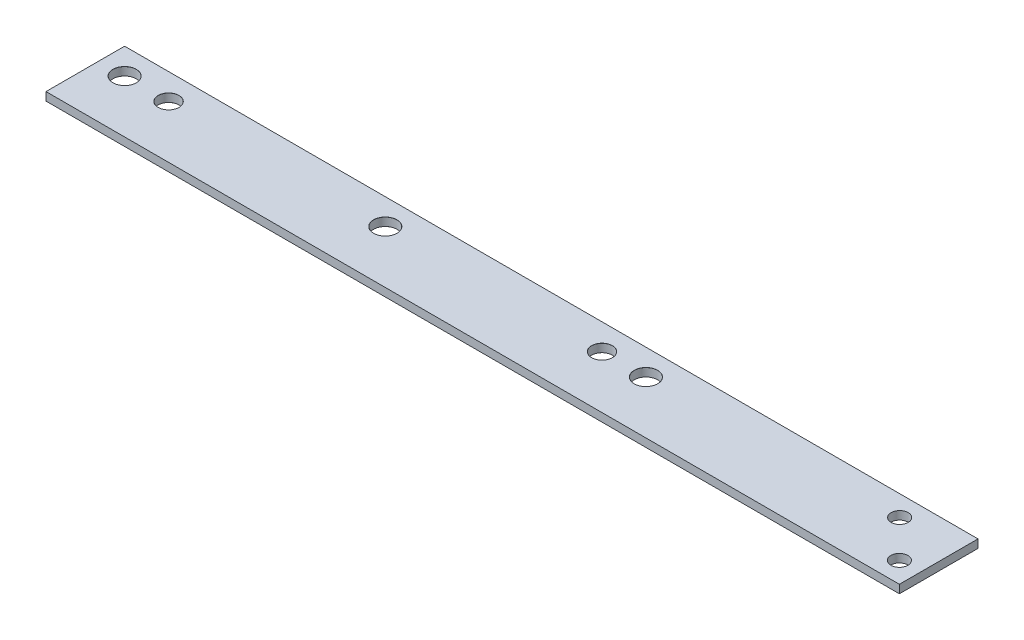
SolidWorks part; units mm, degrees
material "1.2316 (X36CrMo17)"
ref_plane "Front Plane" through (0, 0, 0) normal (0, 0, 1) x (1, 0, 0)
ref_plane "Top Plane" through (0, 0, 0) normal (0, 1, 0) x (1, 0, 0)
ref_plane "Right Plane" through (0, 0, 0) normal (1, 0, 0) x (0, 0, -1)
sketch "Sketch1" plane through (0, 0, 0) normal (0, 1, 0) x (1, 0, 0)
  line L1 (-165, 15.2) -> (165, 15.2)
  line L2 (-165, 15.2) -> (-165, -15.2)
  line L3 (-165, -15.2) -> (165, -15.2)
  line L4 (165, 15.2) -> (165, -15.2)
  line L5 (-165, 15.2) -> (165, -15.2) construction
  line L6 (-165, -15.2) -> (165, 15.2) construction
  point P0 (0, 0)
  dimension "D1" = 30.4
  dimension "D2" = 330
extrude "Boss-Extrude1" add sketch "Sketch1" against normal blind 3.2
sketch "Sketch2" plane through (0, 0, 0) normal (0, 1, 0) x (1, 0, 0)
  point P0 (-155, 5.2)
  point P3 (46.6, 5.2)
  point P6 (-54.2, 5.2)
hole_wizard "M8 Clearance Hole1" positions "Sketch2" profile "Sketch3" hole size "M8" standard "ISO" end condition through all
sketch "Sketch3" plane through (-155, 0, -5.2) normal (1, 0, 0) x (0, 0, 1)
  line L0 (0, 0) -> (0, 3.2)
  line L1 (0, 3.2) -> (4.525, 3.2)
  line L2 (4.5, 3.175) -> (4.5, 0.025)
  line L3 (4.5, 0.025) -> (4.525, 0)
  line L5 (4.525, 0) -> (0, 0)
  line L6 (-4.5, 0.025) -> (-4.525, 0) construction
  line L7 (4.525, 3.2) -> (4.5, 3.175)
  line L8 (-4.525, 3.2) -> (-4.5, 3.175) construction
  line L11 (0, -6.35) -> (0, 107.95) construction
  dimension "Thru Hole Dia." = 9
  dimension "Thru Hole Depth" = 3.2
  dimension "Near C'Sink Dia." = 9.05
  dimension "Near C'Sink Angle" = 90
  dimension "Far C'Sink Dia." = 9.05
  dimension "Far C'Sink Angle" = 90
sketch "Sketch4" plane through (0, 0, 0) normal (0, 1, 0) x (1, 0, 0)
  point P0 (-138, 5.2)
  point P3 (29.6, 5.2)
hole_wizard "Ø8.0mm Dowel Hole1" positions "Sketch4" profile "Sketch5" hole size "Ø8.0" standard "ISO" end condition through all
sketch "Sketch5" plane through (-138, 0, -5.2) normal (1, 0, 0) x (0, 0, 1)
  line L0 (0, 0) -> (0, 3.2)
  line L1 (0, 3.2) -> (4.025, 3.2)
  line L2 (4, 3.175) -> (4, 0.025)
  line L3 (4, 0.025) -> (4.025, 0)
  line L5 (4.025, 0) -> (0, 0)
  line L6 (-4, 0.025) -> (-4.025, 0) construction
  line L7 (4.025, 3.2) -> (4, 3.175)
  line L8 (-4.025, 3.2) -> (-4, 3.175) construction
  line L11 (0, -6.35) -> (0, 107.95) construction
  dimension "Thru Hole Dia." = 8
  dimension "Thru Hole Depth" = 3.2
  dimension "Near C'Sink Dia." = 8.05
  dimension "Near C'Sink Angle" = 90
  dimension "Far C'Sink Dia." = 8.05
  dimension "Far C'Sink Angle" = 90
sketch "Sketch8" plane through (0, 0, 0) normal (0, 1, 0) x (1, 0, 0)
  point P0 (142.7, 7.2)
  point P3 (157, -7.2)
hole_wizard "M6 Clearance Hole1" positions "Sketch8" profile "Sketch9" hole size "M6" standard "ISO" end condition through all
sketch "Sketch9" plane through (142.7, 0, -7.2) normal (1, 0, 0) x (0, 0, 1)
  line L0 (0, 0) -> (0, 3.2)
  line L1 (0, 3.2) -> (3.3, 3.2)
  line L2 (3.3, 3.2) -> (3.3, 0)
  line L5 (3.3, 0) -> (0, 0)
  line L11 (0, -6.35) -> (0, 107.95) construction
  dimension "Thru Hole Dia." = 6.6
  dimension "Thru Hole Depth" = 3.2
